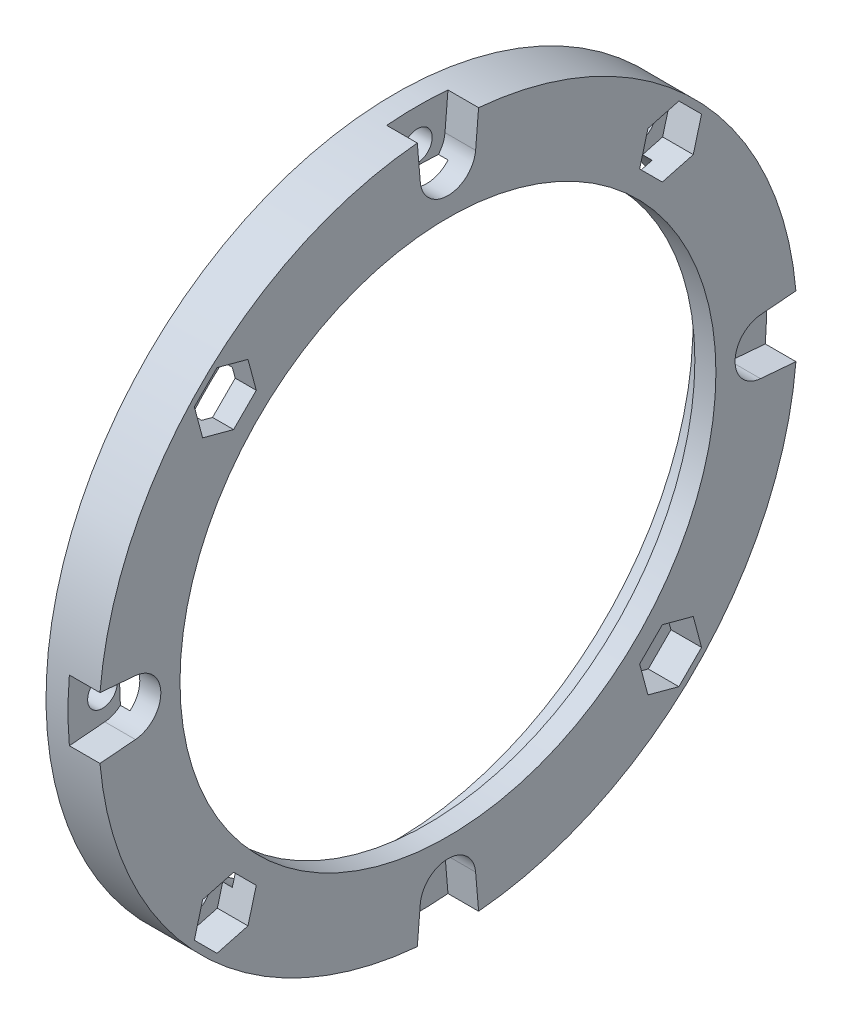
SolidWorks part; units mm, degrees
material "聚脂树脂"
ref_plane "前视基准面" through (0, 0, 0) normal (0, 0, 1) x (1, 0, 0)
ref_plane "上视基准面" through (0, 0, 0) normal (0, 1, 0) x (1, 0, 0)
ref_plane "右视基准面" through (0, 0, 0) normal (1, 0, 0) x (0, 0, -1)
sketch "草图1" plane through (0, 0, 0) normal (1, 0, 0) x (0, 0, -1)
  circle A0 centre (0, 0) radius 36.5
  circle A1 centre (0, 0) radius 28
  dimension "D1" = 73
  dimension "D2" = 56
extrude "凸台-拉伸1" add sketch "草图1" along normal blind 5.5
sketch "草图2" plane through (0, 0, 0) normal (-1, 0, 0) x (0, 0, 1)
  circle A0 centre (0, 0) radius 31.1
  dimension "D1" = 62.2
extrude "切除-拉伸1" cut sketch "草图2" against normal blind 3.3
sketch "草图3" plane through (5.5, 0, 0) normal (1, 0, 0) x (0, 0, -1)
  line L0 (0, 0) -> (32.9, 0)
  circle A0 centre (32.9, 0) radius 1.55
  circle A1 centre (23.2638, -23.2638) radius 1.55
  circle A2 centre (0, -32.9) radius 1.55
  circle A3 centre (-23.2638, -23.2638) radius 1.55
  circle A4 centre (-32.9, 0) radius 1.55
  circle A5 centre (-23.2638, 23.2638) radius 1.55
  circle A6 centre (0, 32.9) radius 1.55
  circle A7 centre (23.2638, 23.2638) radius 1.55
  point P20 (0, 0)
  dimension "D1" = 3.1
  dimension "D2" = 32.9
  dimension "D3" = 8
extrude "切除-拉伸2" cut sketch "草图3" against normal up to next contours A6 | A7 | A0 | A1 | A5 | A4 | A3 | A2
sketch "草图4" plane through (5.5, 0, 0) normal (1, 0, 0) x (0, 0, -1)
  line L0 (32.6568, 2.8898) -> (36.3593, 3.2014)
  line L1 (32.6568, -2.8898) -> (36.3593, -3.2014)
  line L2 (2.8898, -32.6568) -> (3.2014, -36.3593)
  line L3 (-2.8898, -32.6568) -> (-3.2014, -36.3593)
  line L4 (28.5155, -22.7841) -> (28.6206, -22.8684)
  line L5 (22.9347, -28.3945) -> (23.0059, -28.4832)
  line L6 (4.2057, -36.2569) -> (4.2244, -36.4278)
  line L7 (-3.7033, -36.3116) -> (-3.7161, -36.4278)
  line L8 (-22.5579, -28.6948) -> (-22.6143, -28.765)
  line L9 (-28.223, -23.1454) -> (-28.229, -23.1503)
  line L10 (-32.6568, -2.8898) -> (-36.3593, -3.2014)
  line L11 (-32.6568, 2.8898) -> (-36.3593, 3.2014)
  line L12 (-2.8898, 32.6568) -> (-3.2014, 36.3593)
  line L13 (2.8898, 32.6568) -> (3.2014, 36.3593)
  line L14 (0, 0) -> (23.2638, -23.2638) construction
  line L15 (25.6317, -20.896) -> (22.3971, -20.0293)
  line L16 (22.3971, -20.0293) -> (20.0293, -22.3971)
  line L17 (20.0293, -22.3971) -> (20.896, -25.6317)
  line L18 (20.896, -25.6317) -> (24.1305, -26.4983)
  line L19 (24.1305, -26.4983) -> (26.4983, -24.1305)
  line L20 (26.4983, -24.1305) -> (25.6317, -20.896)
  line L21 (-20.896, -25.6317) -> (-20.0293, -22.3971)
  line L22 (-20.0293, -22.3971) -> (-22.3971, -20.0293)
  line L23 (-22.3971, -20.0293) -> (-25.6317, -20.896)
  line L24 (-25.6317, -20.896) -> (-26.4983, -24.1305)
  line L25 (-26.4983, -24.1305) -> (-24.1305, -26.4983)
  line L26 (-24.1305, -26.4983) -> (-20.896, -25.6317)
  line L27 (-25.6317, 20.896) -> (-22.3971, 20.0293)
  line L28 (-22.3971, 20.0293) -> (-20.0293, 22.3971)
  line L29 (-20.0293, 22.3971) -> (-20.896, 25.6317)
  line L30 (-20.896, 25.6317) -> (-24.1305, 26.4983)
  line L31 (-24.1305, 26.4983) -> (-26.4983, 24.1305)
  line L32 (-26.4983, 24.1305) -> (-25.6317, 20.896)
  line L33 (20.896, 25.6317) -> (20.0293, 22.3971)
  line L34 (20.0293, 22.3971) -> (22.3971, 20.0293)
  line L35 (22.3971, 20.0293) -> (25.6317, 20.896)
  line L36 (25.6317, 20.896) -> (26.4983, 24.1305)
  line L37 (26.4983, 24.1305) -> (24.1305, 26.4983)
  line L38 (24.1305, 26.4983) -> (20.896, 25.6317)
  circle A1 centre (0, 0) radius 36.5
  arc A2 (2.8898, -32.6568) -> (-2.8898, -32.6568) centre (0, -32.9) ccw
  arc A3 (-32.6568, -2.8898) -> (-32.6568, 2.8898) centre (-32.9, 0) ccw
  arc A4 (-2.8898, 32.6568) -> (2.8898, 32.6568) centre (0, 32.9) ccw
  circle A6 centre (23.2638, -23.2638) radius 2.9807 construction
  arc A9 (32.6568, 2.8898) -> (32.6568, -2.8898) centre (32.9, 0) ccw
  point P38 (0, 0)
  point P48 (0.0549, -0.1993)
  point P67 (0, 0)
  point P83 (0, 0)
  circle M7 centre (0, 32.9) radius 1.55
  circle M8 centre (0, -32.9) radius 1.55
  circle M10 centre (-32.9, 0) radius 1.55
  circle M11 centre (23.2638, 23.2638) radius 1.55
  circle M12 centre (32.9, 0) radius 1.55
  circle M13 centre (23.2638, -23.2638) radius 1.55
  circle M15 centre (0, 0) radius 36.5
  dimension "D1" = 73
  dimension "D2" = 5.8
  dimension "D3" = 4
  dimension "D4" = 5.8
  dimension "D5" = 4
extrude "切除-拉伸3" cut sketch "草图4" against normal blind 3.2 contours L10 A3 L11 M15 M10 | L12 A4 L13 M15 M7 | L37 L38 L33 L34 L35 L36 M11 | L0 A9 L1 M15 M12 | L19 L20 L15 L16 L17 L18 M13 | L2 A2 L3 M15 M8 | L21 L22 L23 L24 L25 L26 | L29 L30 L31 L32 L27 L28
